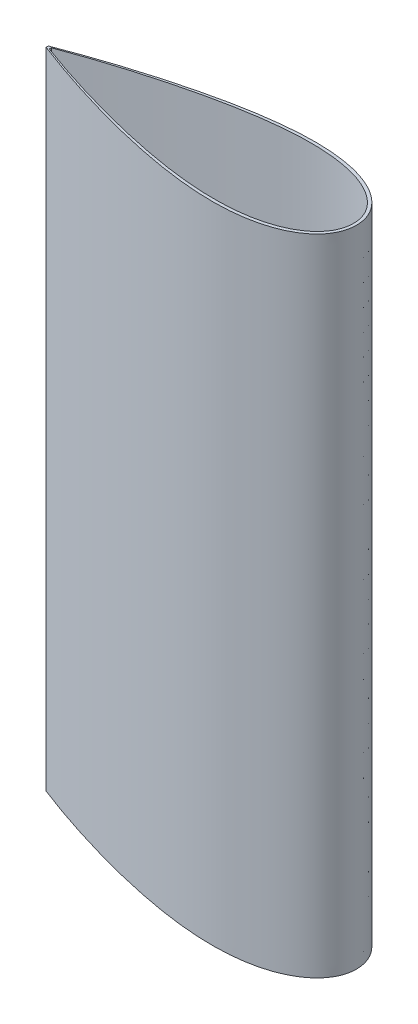
SolidWorks part; units mm, degrees
ref_plane "Front Plane" through (0, 0, 0) normal (0, 0, 1) x (1, 0, 0)
ref_plane "Top Plane" through (0, 0, 0) normal (0, 1, 0) x (1, 0, 0)
ref_plane "Right Plane" through (0, 0, 0) normal (1, 0, 0) x (0, 0, -1)
sketch "Sketch1" plane through (0, 0, 0) normal (0, 1, 0) x (1, 0, 0)
  line L0 (-57.12, 0.2856) -> (-57.12, -0.2856)
  spline S0 degree 3 poles (-57.12, 0.2856) (-57.0455, 0.3146) (-56.7485, 0.4302) (-56.0834, 0.6871) (-54.983, 1.1068) (-53.4592, 1.6765) (-51.5286, 2.3803) (-49.2122, 3.199) (-46.5354, 4.1118) (-43.5275, 5.0968) (-40.2216, 6.1313) (-36.6538, 7.1921) (-32.8633, 8.2555) (-28.8918, 9.2967) (-24.7825, 10.2896) (-20.5805, 11.2067) (-16.3315, 12.0191) (-12.0818, 12.6971) (-7.8773, 13.2115) (-3.7637, 13.5344) (0.2146, 13.6416) (4.0146, 13.5139) (7.5949, 13.1388) (10.9168, 12.5117) (13.9444, 11.6361) (16.6449, 10.5233) (18.9894, 9.1906) (20.9528, 7.6588) (22.5125, 5.9493) (23.6466, 4.0829) (24.3334, 2.0807) (24.5534, 0) (24.3334, -2.0807) (23.6466, -4.0829) (22.5125, -5.9493) (20.9528, -7.6588) (18.9894, -9.1906) (16.6449, -10.5233) (13.9444, -11.6361) (10.9168, -12.5117) (7.5949, -13.1388) (4.0146, -13.5139) (0.2146, -13.6416) (-3.7637, -13.5344) (-7.8773, -13.2115) (-12.0818, -12.6971) (-16.3315, -12.0191) (-20.5805, -11.2067) (-24.7825, -10.2896) (-28.8918, -9.2967) (-32.8633, -8.2555) (-36.6538, -7.1921) (-40.2216, -6.1313) (-43.5275, -5.0968) (-46.5354, -4.1118) (-49.2122, -3.199) (-51.5286, -2.3803) (-53.4592, -1.6765) (-54.983, -1.1068) (-56.0834, -0.6871) (-56.7485, -0.4302) (-57.0455, -0.3146) (-57.12, -0.2856) knots 0 0 0 0 0.001336 0.005324 0.011911 0.02101 0.032502 0.04624 0.062053 0.079748 0.099113 0.119921 0.141927 0.164878 0.188508 0.212546 0.236722 0.260767 0.284427 0.307466 0.329675 0.350878 0.370938 0.389758 0.407281 0.423498 0.43844 0.452198 0.464931 0.47689 0.488429 0.5 0.511571 0.52311 0.535069 0.547802 0.56156 0.576502 0.592719 0.610242 0.629062 0.649122 0.670325 0.692534 0.715573 0.739233 0.763278 0.787454 0.811492 0.835122 0.858073 0.880079 0.900887 0.920252 0.937947 0.95376 0.967498 0.97899 0.988089 0.994676 0.998664 1 1 1 1
extrude "Boss-Extrude1" add sketch "Sketch1" along normal blind 170
sketch "Sketch2" plane through (0, 0, 0) normal (0, 1, 0) x (1, 0, 0)
  line L0 (-56.32, 0.2688) -> (-56.32, -0.2688)
  spline S0 degree 3 poles (-56.32, 0.2688) (-56.247, 0.2961) (-55.9558, 0.4049) (-55.3037, 0.6468) (-54.2248, 1.0418) (-52.7308, 1.5781) (-50.8379, 2.2406) (-48.5669, 3.0112) (-45.9425, 3.8705) (-42.9936, 4.7976) (-39.7524, 5.7714) (-36.2545, 6.7699) (-32.5383, 7.7708) (-28.6445, 8.7509) (-24.6158, 9.6854) (-20.4961, 10.5487) (-16.3304, 11.3133) (-12.164, 11.9516) (-8.0422, 12.4357) (-4.0094, 12.7396) (-0.1096, 12.8404) (3.6152, 12.7202) (7.1244, 12.3673) (10.3802, 11.7774) (13.3472, 10.9539) (15.9936, 9.9075) (18.2913, 8.6544) (20.216, 7.2141) (21.746, 5.6063) (22.86, 3.8494) (23.5355, 1.9624) (23.7522, 0) (23.5355, -1.9624) (22.86, -3.8494) (21.746, -5.6063) (20.216, -7.2141) (18.2913, -8.6544) (15.9936, -9.9075) (13.3472, -10.9539) (10.3802, -11.7774) (7.1244, -12.3673) (3.6152, -12.7202) (-0.1096, -12.8404) (-4.0094, -12.7396) (-8.0422, -12.4357) (-12.164, -11.9516) (-16.3304, -11.3133) (-20.4961, -10.5487) (-24.6158, -9.6854) (-28.6445, -8.7509) (-32.5383, -7.7708) (-36.2545, -6.7699) (-39.7524, -5.7714) (-42.9936, -4.7976) (-45.9425, -3.8705) (-48.5669, -3.0112) (-50.8379, -2.2406) (-52.7308, -1.5781) (-54.2248, -1.0418) (-55.3037, -0.6468) (-55.9558, -0.4049) (-56.247, -0.2961) (-56.32, -0.2688) knots 0 0 0 0 0.001336 0.005327 0.011918 0.021024 0.032528 0.046283 0.06212 0.079847 0.099254 0.120113 0.14218 0.165202 0.188914 0.213046 0.237324 0.261482 0.285262 0.308426 0.33076 0.352081 0.372245 0.391144 0.408713 0.424926 0.439806 0.453432 0.465957 0.477632 0.488823 0.5 0.511177 0.522368 0.534043 0.546568 0.560194 0.575074 0.591287 0.608856 0.627755 0.647919 0.66924 0.691574 0.714738 0.738518 0.762676 0.786954 0.811086 0.834798 0.85782 0.879887 0.900746 0.920153 0.93788 0.953717 0.967472 0.978976 0.988082 0.994673 0.998664 1 1 1 1
extrude "Cut-Extrude1" cut sketch "Sketch2" against normal through all and the other way through all
